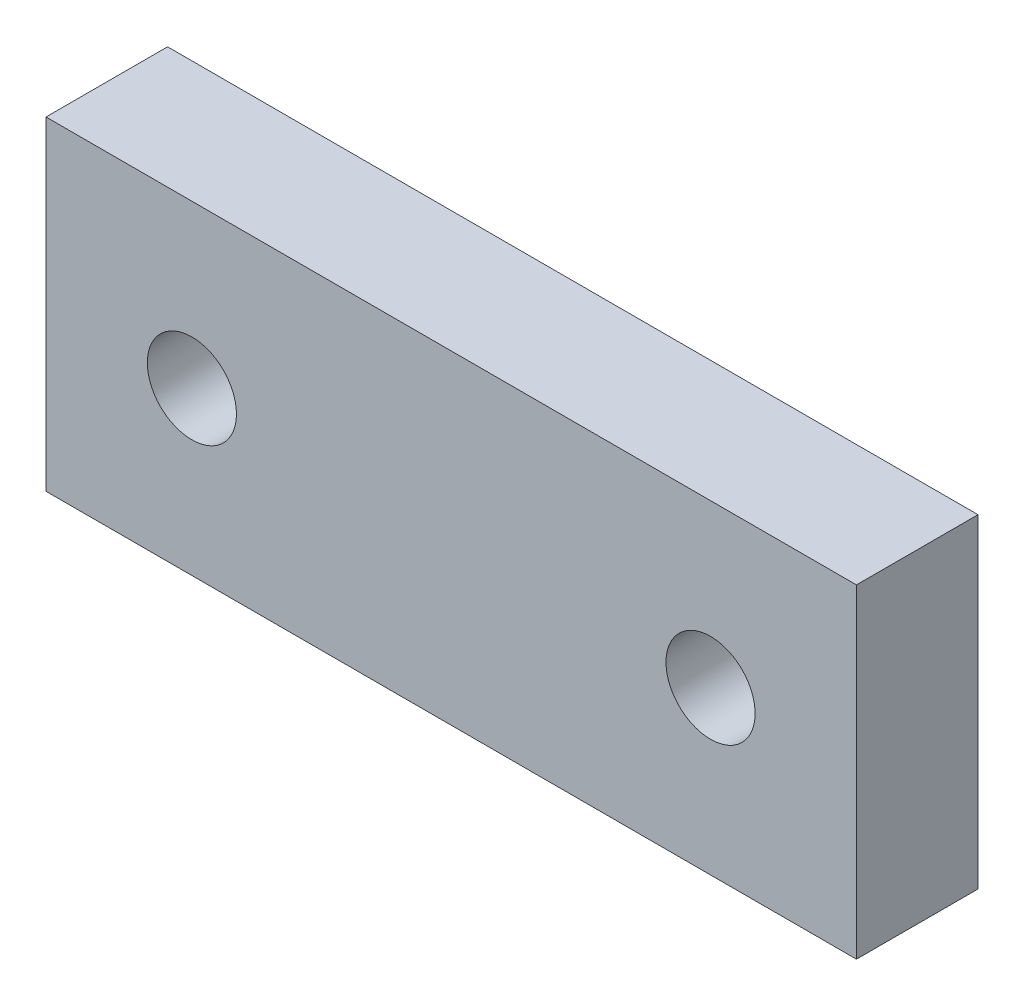
SolidWorks part; units mm, degrees
ref_plane "前视基准面" through (0, 0, 0) normal (0, 0, 1) x (1, 0, 0)
ref_plane "上视基准面" through (0, 0, 0) normal (0, 1, 0) x (1, 0, 0)
ref_plane "右视基准面" through (0, 0, 0) normal (1, 0, 0) x (0, 0, -1)
other "Configuration Table"
sketch "草图1" plane through (0, 0, 0) normal (0, 0, 1) x (1, 0, 0)
  line L0 (0, -10) -> (0, 10) construction
  line L1 (-25, -10) -> (25, -10)
  line L2 (-25, -10) -> (-25, 10)
  line L3 (-25, 10) -> (25, 10)
  line L4 (25, -10) -> (25, 10)
  line L5 (-25, -10) -> (25, 10) construction
  line L6 (-25, 10) -> (25, -10) construction
  circle A0 centre (-16, 0) radius 2.75
  circle A1 centre (16, 0) radius 2.75
  point P0 (0, 0)
  dimension "D3" = 5.5
  dimension "D4" = 16
  dimension "D1" = 20
  dimension "D2" = 50
extrude "凸台-拉伸1" add sketch "草图1" along normal blind 7.5
